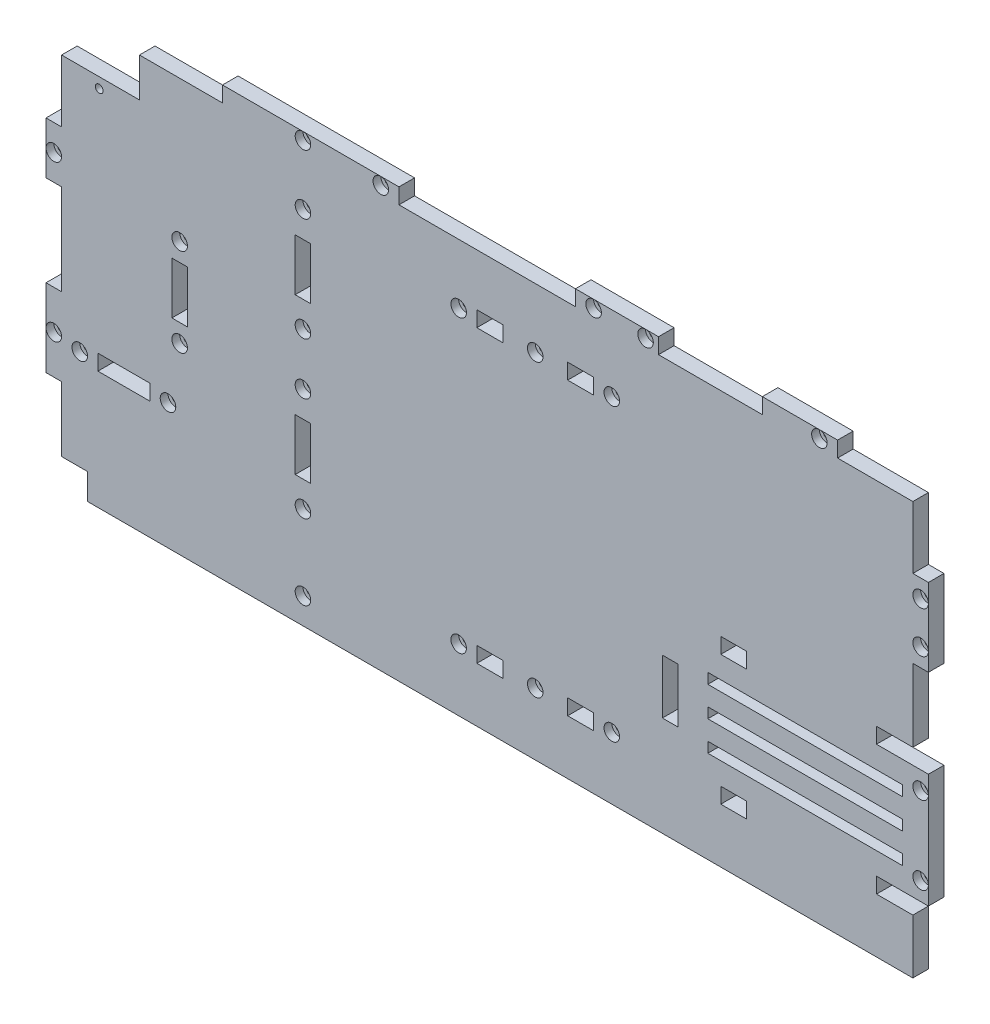
SolidWorks part; units mm, degrees
ref_plane "Plan de face" through (0, 0, 0) normal (0, 0, 1) x (1, 0, 0)
ref_plane "Plan de dessus" through (0, 0, 0) normal (0, 1, 0) x (1, 0, 0)
ref_plane "Plan de droite" through (0, 0, 0) normal (1, 0, 0) x (0, 0, -1)
sketch "Esquisse1" plane through (0, 0, 0) normal (0, 0, 1) x (1, 0, 0)
  line L1 (0, 0) -> (-340, 0)
  line L2 (0, 0) -> (0, 148)
  line L3 (0, 148) -> (-340, 148)
  line L4 (-340, 0) -> (-340, 148)
  dimension "D1" = 148
  dimension "D2" = 340
extrude "Boss.-Extru.1" add sketch "Esquisse1" along normal blind 6
sketch "Esquisse2" plane through (0, 0, 6) normal (0, 0, 1) x (1, 0, 0)
  line L0 (0, 0) -> (0, 148) construction
  line L1 (0, 148) -> (-340, 148) construction
  line L2 (-272, 142) -> (-334, 142)
  line L3 (-334, 142) -> (-334, 103)
  line L4 (0, 148) -> (0, 118)
  line L5 (0, 0) -> (-6, 0)
  line L6 (-340, 148) -> (-272, 148)
  line L7 (0, 0) -> (0, 10)
  line L8 (-340, 48) -> (-334, 48)
  line L9 (-334, 103) -> (-340, 103)
  line L10 (-340, 148) -> (-340, 0) construction
  line L11 (-340, 0) -> (-334, 0)
  line L12 (-340, 0) -> (-340, 18)
  line L13 (0, 10) -> (-6, 10)
  line L14 (-272, 148) -> (-272, 142)
  line L15 (-204, 148) -> (-136, 148)
  line L16 (-204, 148) -> (-204, 142)
  line L17 (-204, 142) -> (-136, 142)
  line L18 (-6, 0) -> (-6, 10)
  line L19 (0, 54) -> (-6, 54)
  line L20 (0, 54) -> (0, 88)
  line L21 (0, 88) -> (-6, 88)
  line L22 (-136, 148) -> (-136, 142)
  line L23 (0, 148) -> (-35, 148)
  line L24 (-340, 18) -> (-334, 18)
  line L25 (-6, 142) -> (-35, 142)
  line L26 (-35, 148) -> (-35, 142)
  line L27 (-334, 0) -> (-334, 18)
  line L28 (-340, 103) -> (-340, 148)
  line L29 (-6, 54) -> (-6, 88)
  line L30 (-334, 48) -> (-334, 83)
  line L31 (-334, 83) -> (-340, 83)
  line L32 (0, 118) -> (-6, 118)
  line L33 (-6, 142) -> (-6, 118)
  line L34 (-340, 83) -> (-340, 48)
  line L36 (-64, 148) -> (-104, 148)
  line L37 (-64, 148) -> (-64, 142)
  line L38 (-64, 142) -> (-104, 142)
  line L39 (-104, 148) -> (-104, 142)
  dimension "D3" = 68
  dimension "D4" = 6
  dimension "D5" = 35
  dimension "D6" = 32
  dimension "D7" = 30
  dimension "D8" = 6
  dimension "D9" = 30
  dimension "D10" = 44
  dimension "D11" = 24
  dimension "D12" = 34
  dimension "D13" = 6
  dimension "D14" = 68
  dimension "D15" = 6
  dimension "D16" = 6
  dimension "D17" = 20
  dimension "D18" = 6
  dimension "D19" = 18
  dimension "D20" = 6
  dimension "D21" = 6
  dimension "D22" = 35
  dimension "D23" = 40
  dimension "D24" = 29
extrude "Enlèv. mat.-Extru.1" cut sketch "Esquisse2" against normal blind 6
sketch "Esquisse3" plane through (0, 0, 6) normal (0, 0, 1) x (1, 0, 0)
  line L0 (-204, 148) -> (-272, 148) construction
  line L1 (-238, 32) -> (-244, 32)
  line L2 (-340, 48) -> (-340, 18) construction
  line L3 (-238, 112) -> (-244, 112)
  line L4 (-238, 112) -> (-238, 92)
  line L5 (-238, 92) -> (-244, 92)
  line L6 (-340, 48) -> (-340, 18) construction
  line L7 (-238, 52) -> (-244, 52)
  line L8 (-238, 52) -> (-238, 32)
  line L9 (-244, 112) -> (-244, 92)
  line L10 (-244, 52) -> (-244, 32)
  line L11 (-285.5, 80.5) -> (-291.5, 80.5)
  line L12 (-334, 0) -> (-6, 0) construction
  line L13 (-285.5, 80.5) -> (-285.5, 60.5)
  line L14 (-285.5, 60.5) -> (-291.5, 60.5)
  line L15 (-291.5, 80.5) -> (-291.5, 60.5)
  line L17 (-334, 142) -> (-272, 142) construction
  line L18 (-334, 142) -> (-304, 142)
  line L19 (-334, 142) -> (-334, 127)
  line L20 (-334, 127) -> (-304, 127)
  line L25 (-300, 34.5) -> (-320, 34.5)
  line L26 (-300, 34.5) -> (-300, 28.5)
  line L27 (-300, 28.5) -> (-320, 28.5)
  line L28 (-320, 34.5) -> (-320, 28.5)
  line L34 (-304, 142) -> (-304, 127)
  dimension "D1" = 20
  dimension "D2" = 20
  dimension "D3" = 40
  dimension "D4" = 96
  dimension "D5" = 96
  dimension "D6" = 6
  dimension "D7" = 6
  dimension "D8" = 92
  dimension "D9" = 6
  dimension "D10" = 20
  dimension "D11" = 48.5
  dimension "D12" = 67.5
  dimension "D13" = 107.5
  dimension "D14" = 15
  dimension "D15" = 30
  dimension "D19" = 20
  dimension "D20" = 6
  dimension "D22" = 20
extrude "Enlèv. mat.-Extru.2" cut sketch "Esquisse3" against normal blind 10
sketch "Esquisse4" plane through (0, 0, 6) normal (0, 0, 1) x (1, 0, 0)
  line L1 (-164, 122) -> (-174, 122)
  line L2 (-164, 122) -> (-164, 116)
  line L3 (-164, 116) -> (-174, 116)
  line L4 (-174, 122) -> (-174, 116)
  line L5 (-204, 148) -> (-272, 148) construction
  line L6 (-35, 148) -> (-64, 148) construction
  line L7 (-139, 122) -> (-129, 122)
  line L8 (-139, 122) -> (-139, 116)
  line L9 (-139, 116) -> (-129, 116)
  line L10 (-129, 122) -> (-129, 116)
  line L11 (-340, 103) -> (-340, 83) construction
  line L12 (-129, 10) -> (-139, 10)
  line L13 (-129, 10) -> (-129, 4)
  line L14 (-129, 4) -> (-139, 4)
  line L15 (-139, 10) -> (-139, 4)
  line L16 (-35, 148) -> (-64, 148) construction
  line L17 (-164, 10) -> (-174, 10)
  line L18 (-164, 10) -> (-164, 4)
  line L19 (-164, 4) -> (-174, 4)
  line L20 (-174, 10) -> (-174, 4)
  line L21 (-204, 148) -> (-272, 148) construction
  line L23 (-340, 48) -> (-340, 18) construction
  circle A0 centre (-151.5, 119) radius 1.5
  circle A1 centre (-151.5, 7) radius 1.5
  dimension "D7" = 3
  dimension "D14" = 138
  dimension "D16" = 3
  dimension "D19" = 3
  dimension "D10" = 3
  dimension "D1" = 10
  dimension "D2" = 6
  dimension "D3" = 166
  dimension "D4" = 26
  dimension "D5" = 10
  dimension "D6" = 25
  dimension "D8" = 12.5
  dimension "D9" = 26
  dimension "D11" = 6
  dimension "D12" = 6
  dimension "D13" = 6
  dimension "D15" = 138
  dimension "D17" = 12.5
  dimension "D18" = 25
  dimension "D20" = 166
  dimension "D21" = 10
  dimension "D22" = 10
extrude "Enlèv. mat.-Extru.3" cut sketch "Esquisse4" against normal blind 10
sketch "Esquisse7" plane through (0, 0, 0) normal (0, -1, 0) x (1, 0, 0)
  line L0 (-334, 6) -> (-6, 6) construction
  line L1 (-334, 6) -> (-6, 6)
  line L2 (-334, 6) -> (-334, 0)
  line L3 (-334, 0) -> (-6, 0)
  line L4 (-6, 6) -> (-6, 0)
  line L5 (-340, 6) -> (-340, 0) construction
  dimension "D1" = 6
extrude "Boss.-Extru.2" add sketch "Esquisse7" along normal blind 17
sketch "Esquisse8" plane through (0, 0, 6) normal (0, 0, 1) x (1, 0, 0)
  line L0 (-241, 115.6483) -> (-241, 35.6483) construction
  line L1 (-334, -17) -> (-324, -17)
  line L2 (-334, -17) -> (-334, -7)
  line L3 (-334, -7) -> (-324, -7)
  line L4 (-324, -17) -> (-324, -7)
  line L5 (-174, 122) -> (-174, 116) construction
  line L6 (-164, 122) -> (-174, 122) construction
  line L9 (-285.5, 80.5) -> (-291.5, 80.5) construction
  line L10 (-285.5, 60.5) -> (-285.5, 80.5) construction
  line L11 (-291.5, 60.5) -> (-285.5, 60.5) construction
  line L12 (-291.5, 80.5) -> (-291.5, 60.5) construction
  line L14 (-300, 28.5) -> (-300, 34.5) construction
  line L15 (-300, 34.5) -> (-320, 34.5) construction
  line L16 (-320, 34.5) -> (-320, 28.5) construction
  line L17 (-340, 48) -> (-340, 18) construction
  line L18 (-334, 18) -> (-340, 18) construction
  line L19 (-204, 148) -> (-272, 148) construction
  line L20 (-238, 112) -> (-244, 112) construction
  line L21 (-244, 92) -> (-238, 92) construction
  line L22 (-238, 52) -> (-244, 52) construction
  line L23 (-244, 32) -> (-238, 32) construction
  line L24 (-6, -17) -> (-334, -17) construction
  line L26 (-204, 148) -> (-204, 142) construction
  line L27 (-35, 148) -> (-64, 148) construction
  line L28 (-136, 142) -> (-136, 148) construction
  line L29 (-35, 148) -> (-35, 142) construction
  line L30 (-129, 116) -> (-129, 122) construction
  line L31 (-139, 116) -> (-129, 116) construction
  line L32 (-174, 10) -> (-174, 4) construction
  line L33 (-174, 4) -> (-164, 4) construction
  line L34 (-129, 4) -> (-129, 10) construction
  line L35 (-334, 48) -> (-334, 83) construction
  line L36 (-129, 10) -> (-139, 10) construction
  line L37 (0, 88) -> (-6, 88) construction
  line L38 (-340, 103) -> (-340, 83) construction
  line L39 (-6, 88) -> (-6, 54) construction
  line L40 (0, 88) -> (0, 118) construction
  line L41 (-6, 118) -> (0, 118) construction
  line L42 (0, 10) -> (0, 54) construction
  line L43 (-6, 54) -> (0, 54) construction
  line L44 (-340, 103) -> (-334, 103) construction
  line L45 (0, 10) -> (-6, 10) construction
  circle A0 centre (-42, 145) radius 1.5
  circle A1 centre (-129, 145) radius 1.5
  circle A2 centre (-109, 145) radius 1.5
  circle A3 centre (-3, 111) radius 1.5
  circle A4 centre (-3, 95) radius 1.5
  circle A5 centre (-3, 47) radius 1.5
  circle A6 centre (-3, 17) radius 1.5
  circle A7 centre (-122, 119) radius 1.5
  circle A8 centre (-181, 119) radius 1.5
  circle A9 centre (-122, 7) radius 1.5
  circle A10 centre (-181, 7) radius 1.5
  circle A11 centre (-211, 145) radius 1.5
  circle A12 centre (-241, 145) radius 1.5
  circle A13 centre (-241, 122) radius 1.5
  circle A14 centre (-241, 82) radius 1.5
  circle A15 centre (-241, 62) radius 1.5
  circle A16 centre (-241, 22) radius 1.5
  circle A17 centre (-241, -7) radius 1.5
  circle A18 centre (-288.5, 87.5) radius 1.5
  circle A19 centre (-288.5, 53.5) radius 1.5
  circle A20 centre (-319.5, 123) radius 1.5
  circle A22 centre (-293, 31.5) radius 1.5
  circle A23 centre (-327, 31.5) radius 1.5
  circle A24 centre (-337, 33) radius 1.5
  circle A25 centre (-337, 93) radius 1.5
  point P105 (-35, 145)
  point P118 (-3, 10)
  dimension "D5" = 3
  dimension "D6" = 3
  dimension "D7" = 3
  dimension "D8" = 3
  dimension "D9" = 3
  dimension "D10" = 3
  dimension "D12" = 7
  dimension "D13" = 3
  dimension "D14" = 7
  dimension "D15" = 3
  dimension "D18" = 7
  dimension "D19" = 3
  dimension "D20" = 7
  dimension "D21" = 3
  dimension "D22" = 3
  dimension "D23" = 15
  dimension "D24" = 3
  dimension "D25" = 3
  dimension "D26" = 3
  dimension "D27" = 10
  dimension "D28" = 3
  dimension "D29" = 10
  dimension "D30" = 3
  dimension "D31" = 10
  dimension "D32" = 3
  dimension "D33" = 10
  dimension "D34" = 3
  dimension "D35" = 10
  dimension "D37" = 3
  dimension "D38" = 7
  dimension "D39" = 3
  dimension "D40" = 3
  dimension "D41" = 7
  dimension "D42" = 3
  dimension "D43" = 3
  dimension "D44" = 3
  dimension "D45" = 7
  dimension "D46" = 3
  dimension "D47" = 3
  dimension "D48" = 3
  dimension "D50" = 7
  dimension "D52" = 3
  dimension "D53" = 7
  dimension "D54" = 3
  dimension "D55" = 3
  dimension "D56" = 7
  dimension "D57" = 3
  dimension "D58" = 7
  dimension "D59" = 3
  dimension "D60" = 3
  dimension "D61" = 3
  dimension "D62" = 7
  dimension "D63" = 3
  dimension "D64" = 3
  dimension "D65" = 3
  dimension "D66" = 7
  dimension "D67" = 3
  dimension "D68" = 3
  dimension "D69" = 7
  dimension "D70" = 3
  dimension "D71" = 7
  dimension "D72" = 3
  dimension "D51" = 20
  dimension "D73" = 3
  dimension "D74" = 3
  dimension "D75" = 10
  dimension "D1" = 10
  dimension "D2" = 10
  dimension "D36" = 93
  dimension "D49" = 3
extrude "Enlèv. mat.-Extru.5" cut sketch "Esquisse8" against normal through all
sketch "Esquisse9" plane through (0, 0, 6) normal (0, 0, 1) x (1, 0, 0)
  circle A0 centre (-337, 33) radius 2.995
  circle A1 centre (-327, 31.5) radius 3
  circle A2 centre (-293, 31.5) radius 3
  circle A3 centre (-288.5, 53.5) radius 3
  circle A4 centre (-288.5, 87.5) radius 3
  circle A7 centre (-241, 145) radius 2.995
  circle A8 centre (-241, 122) radius 2.995
  circle A9 centre (-241, 82) radius 2.995
  circle A10 centre (-241, 62) radius 3
  circle A11 centre (-241, 22) radius 3
  circle A12 centre (-241, -7) radius 3
  circle A13 centre (-211, 145) radius 2.995
  circle A14 centre (-337, 93) radius 2.995
  circle A15 centre (-181, 119) radius 2.995
  circle A16 centre (-151.5, 119) radius 2.995
  circle A17 centre (-129, 145) radius 2.995
  circle A19 centre (-122, 119) radius 2.995
  circle A21 centre (-109, 145) radius 2.995
  circle A23 centre (-122, 7) radius 2.995
  circle A24 centre (-151.5, 7) radius 2.995
  circle A25 centre (-181, 7) radius 2.995
  circle A26 centre (-42, 145) radius 2.995
  circle A27 centre (-3, 111) radius 2.995
  circle A28 centre (-3, 95) radius 2.995
  circle A29 centre (-3, 47) radius 2.995
  circle A30 centre (-3, 17) radius 2.995
  dimension "D1" = 5.99
  dimension "D2" = 5.99
  dimension "D3" = 5.99
  dimension "D4" = 5.99
  dimension "D5" = 5.99
  dimension "D6" = 5.99
  dimension "D7" = 5.99
  dimension "D8" = 5.99
  dimension "D9" = 5.99
  dimension "D10" = 5.99
  dimension "D11" = 5.99
  dimension "D12" = 5.99
  dimension "D13" = 5.99
  dimension "D14" = 5.99
  dimension "D15" = 6
  dimension "D16" = 6
  dimension "D17" = 6
  dimension "D18" = 5.99
  dimension "D19" = 5.99
  dimension "D20" = 5.99
  dimension "D23" = 6
  dimension "D24" = 6
  dimension "D25" = 6
  dimension "D26" = 6
  dimension "D27" = 5.99
  dimension "D28" = 5.99
extrude "Enlèv. mat.-Extru.8" cut sketch "Esquisse9" against normal blind 3
sketch "Esquisse10" plane through (0, 0, 6) normal (0, 0, 1) x (1, 0, 0)
  line L1 (-20, 60) -> (-6, 60)
  line L2 (-6, 88) -> (-6, 54) construction
  line L3 (-6, 60) -> (-6, 54)
  line L4 (-20, 60) -> (-20, 54)
  line L5 (-70, 60) -> (-80, 60)
  line L6 (-70, 60) -> (-70, 54)
  line L7 (-70, 54) -> (-80, 54)
  line L8 (-80, 60) -> (-80, 54)
  line L9 (-6, 54) -> (-20, 54)
  line L10 (-20, 10) -> (-6, 10)
  line L11 (-6, 10) -> (-6, 4)
  line L12 (-20, 10) -> (-20, 4)
  line L13 (-70, 10) -> (-80, 10)
  line L14 (-70, 10) -> (-70, 4)
  line L15 (-70, 4) -> (-80, 4)
  line L16 (-80, 10) -> (-80, 4)
  line L17 (-10, 45.5) -> (-85, 45.5)
  line L18 (-10, 45.5) -> (-10, 41.5)
  line L19 (-10, 41.5) -> (-85, 41.5)
  line L20 (-85, 45.5) -> (-85, 41.5)
  line L21 (-10, 34) -> (-85, 34)
  line L22 (-10, 34) -> (-10, 30)
  line L23 (-10, 30) -> (-85, 30)
  line L24 (-85, 34) -> (-85, 30)
  line L25 (-10, 22.5) -> (-85, 22.5)
  line L26 (-10, 22.5) -> (-10, 18.5)
  line L27 (-10, 18.5) -> (-85, 18.5)
  line L28 (-85, 22.5) -> (-85, 18.5)
  line L29 (-35, 142) -> (-6, 142) construction
  line L31 (0, 10) -> (0, 54) construction
  line L32 (-6, 10) -> (-6, -17) construction
  line L33 (-96.5, 42.5) -> (-102.5, 42.5)
  line L34 (-96.5, 42.5) -> (-96.5, 21.5)
  line L35 (-96.5, 21.5) -> (-102.5, 21.5)
  line L36 (-102.5, 42.5) -> (-102.5, 21.5)
  line L37 (-6, 4) -> (-20, 4)
  dimension "D3" = 50
  dimension "D4" = 14
  dimension "D5" = 6
  dimension "D6" = 6
  dimension "D7" = 10
  dimension "D8" = 82
  dimension "D9" = 14
  dimension "D10" = 44
  dimension "D11" = 6
  dimension "D13" = 6
  dimension "D14" = 10
  dimension "D15" = 50
  dimension "D16" = 44
  dimension "D17" = 4
  dimension "D18" = 4
  dimension "D19" = 4
  dimension "D20" = 75
  dimension "D21" = 75
  dimension "D22" = 75
  dimension "D23" = 10
  dimension "D24" = 10
  dimension "D25" = 10
  dimension "D26" = 7.5
  dimension "D27" = 7.5
  dimension "D29" = 21
  dimension "D30" = 6
  dimension "D31" = 3
  dimension "D32" = 11.5
extrude "Enlèv. mat.-Extru.9" cut sketch "Esquisse10" against normal through all
